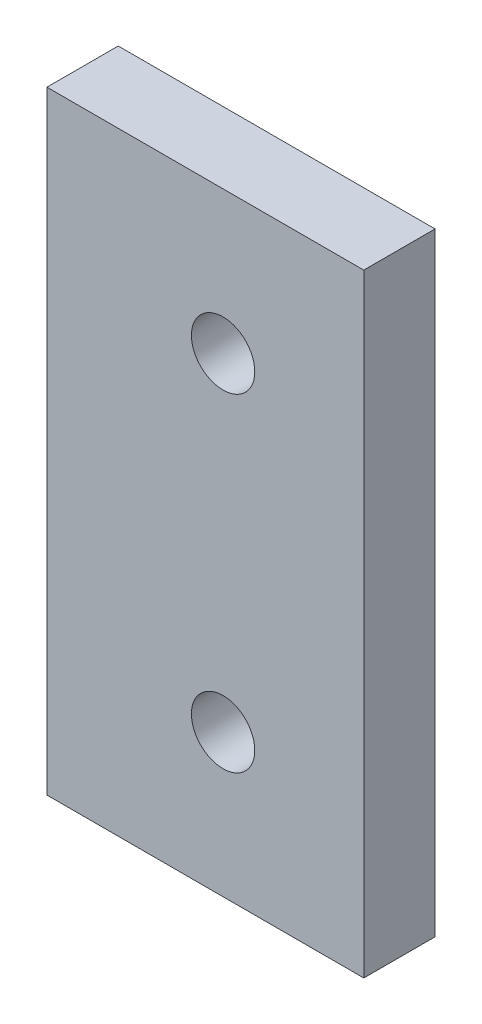
SolidWorks part; units mm, degrees
material "WhitePLA"
ref_plane "Front Plane" through (0, 0, 0) normal (0, 0, 1) x (1, 0, 0)
ref_plane "Top Plane" through (0, 0, 0) normal (0, 1, 0) x (1, 0, 0)
ref_plane "Right Plane" through (0, 0, 0) normal (1, 0, 0) x (0, 0, -1)
sketch "Sketch1" plane through (0, 0, 0) normal (0, 0, 1) x (1, 0, 0)
  line L0 (-11.1183, 29.7) -> (8.8817, 29.7)
  line L1 (8.8817, -9) -> (8.8817, 29.7)
  line L2 (-11.1183, -9) -> (-11.1183, 29.7)
  line L3 (-11.1183, -9) -> (8.8817, -9)
  circle A0 centre (0, 0) radius 2
  circle A1 centre (0, 20.7) radius 2
  dimension "D1" = 4
  dimension "D5" = 20.7
  dimension "D2" = 8.8817
  dimension "D3" = 11.1183
  dimension "D4" = 8.8817
  dimension "D6" = 9
  dimension "D7" = 9
extrude "Boss-Extrude1" add sketch "Sketch1" along normal blind 4.5
